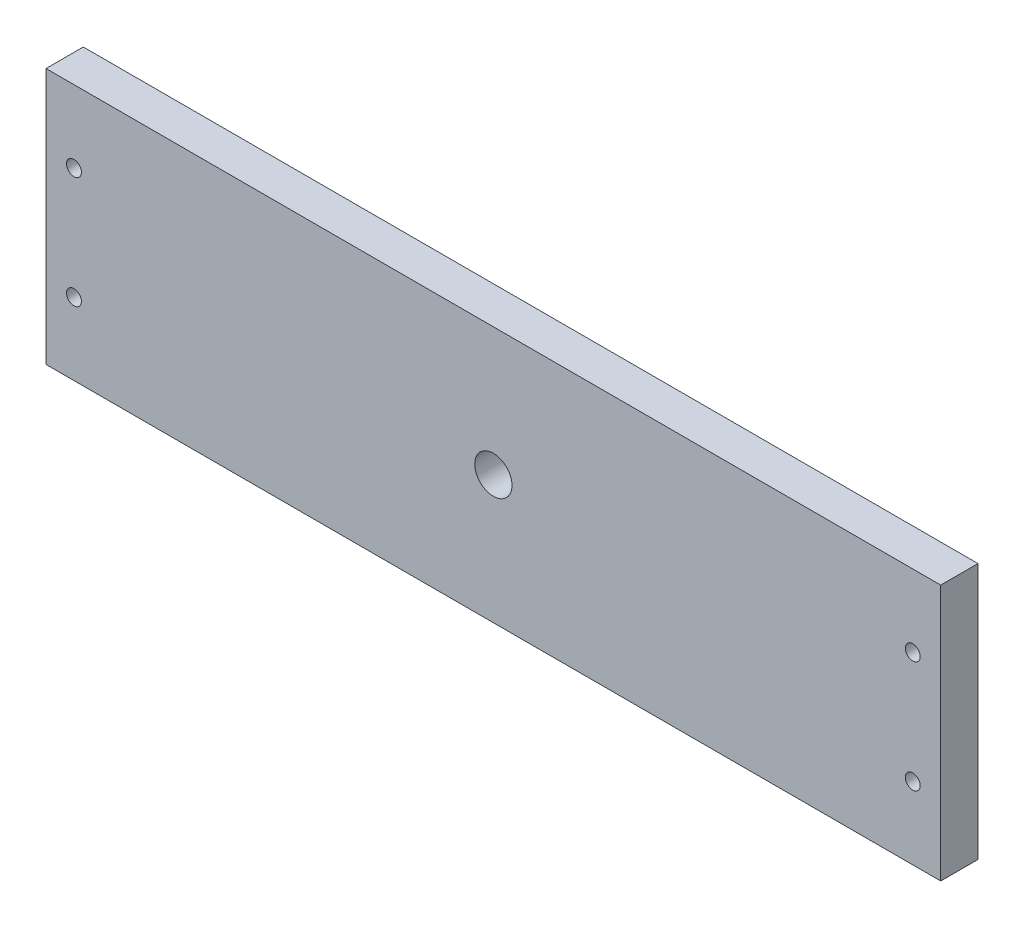
SolidWorks part; units mm, degrees
ref_plane "Front Plane" through (0, 0, 0) normal (0, 0, 1) x (1, 0, 0)
ref_plane "Top Plane" through (0, 0, 0) normal (0, 1, 0) x (1, 0, 0)
ref_plane "Right Plane" through (0, 0, 0) normal (1, 0, 0) x (0, 0, -1)
sketch "Sketch1" plane through (0, 0, 0) normal (0, 0, 1) x (1, 0, 0)
  line L1 (-96, -27.5) -> (96, -27.5)
  line L2 (-96, -27.5) -> (-96, 27.5)
  line L3 (-96, 27.5) -> (96, 27.5)
  line L4 (96, -27.5) -> (96, 27.5)
extrude "Boss-Extrude1" add sketch "Sketch1" along normal blind 8
sketch "Sketch2" plane through (0, 0, 0) normal (0, 0, 1) x (1, 0, 0)
  circle A0 centre (0, 0) radius 4
  circle A1 centre (-90, 12) radius 1.6
  circle A2 centre (-90, -12) radius 1.6
  circle A3 centre (90, 12) radius 1.6
  circle A4 centre (90, -12) radius 1.6
extrude "Cut-Extrude2" cut sketch "Sketch2" along normal blind 9
